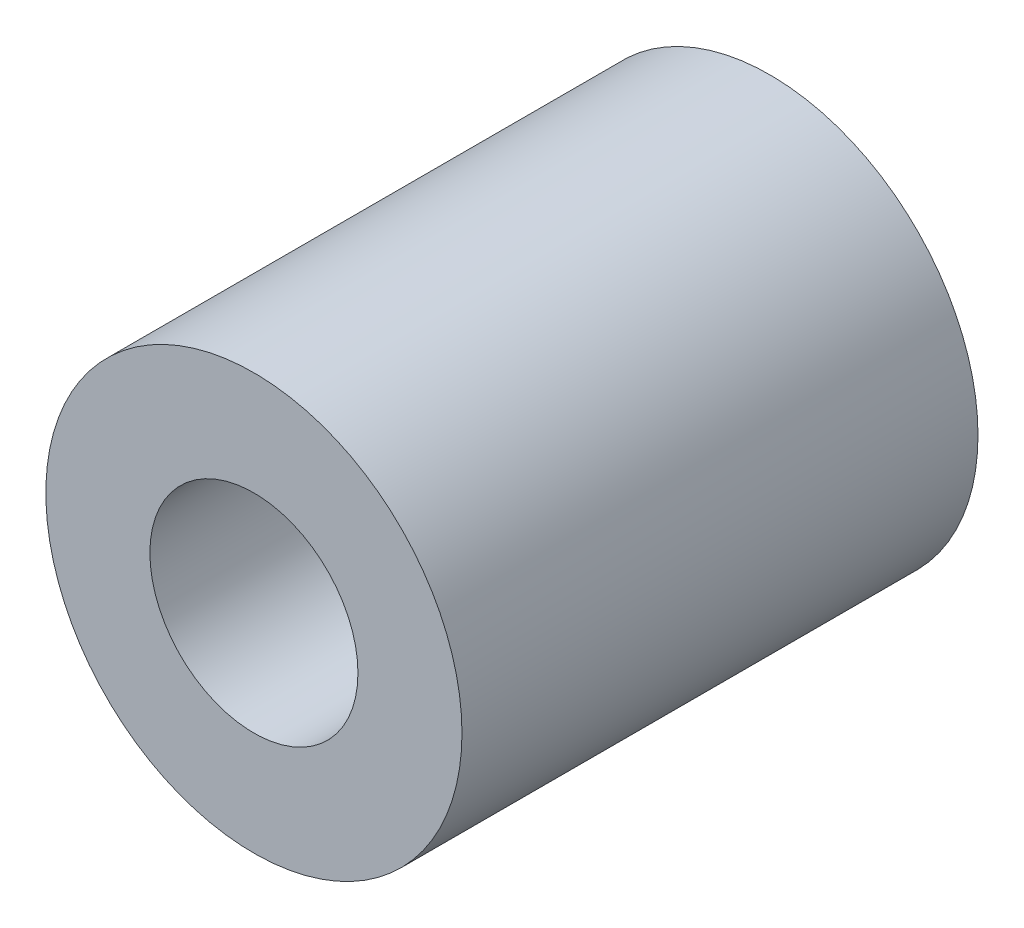
SolidWorks part; units mm, degrees
ref_plane "Front Plane" through (0, 0, 0) normal (0, 0, 1) x (1, 0, 0)
ref_plane "Top Plane" through (0, 0, 0) normal (0, 1, 0) x (1, 0, 0)
ref_plane "Right Plane" through (0, 0, 0) normal (1, 0, 0) x (0, 0, -1)
sketch "Sketch1" plane through (0, 0, 0) normal (0, 0, 1) x (1, 0, 0)
  circle A0 centre (0, 0) radius 6.35
  circle A1 centre (0, 0) radius 3.175
  dimension "D1" = 6.35
  dimension "D2" = 12.7
extrude "Boss-Extrude1" add sketch "Sketch1" along normal mid plane 15.748
